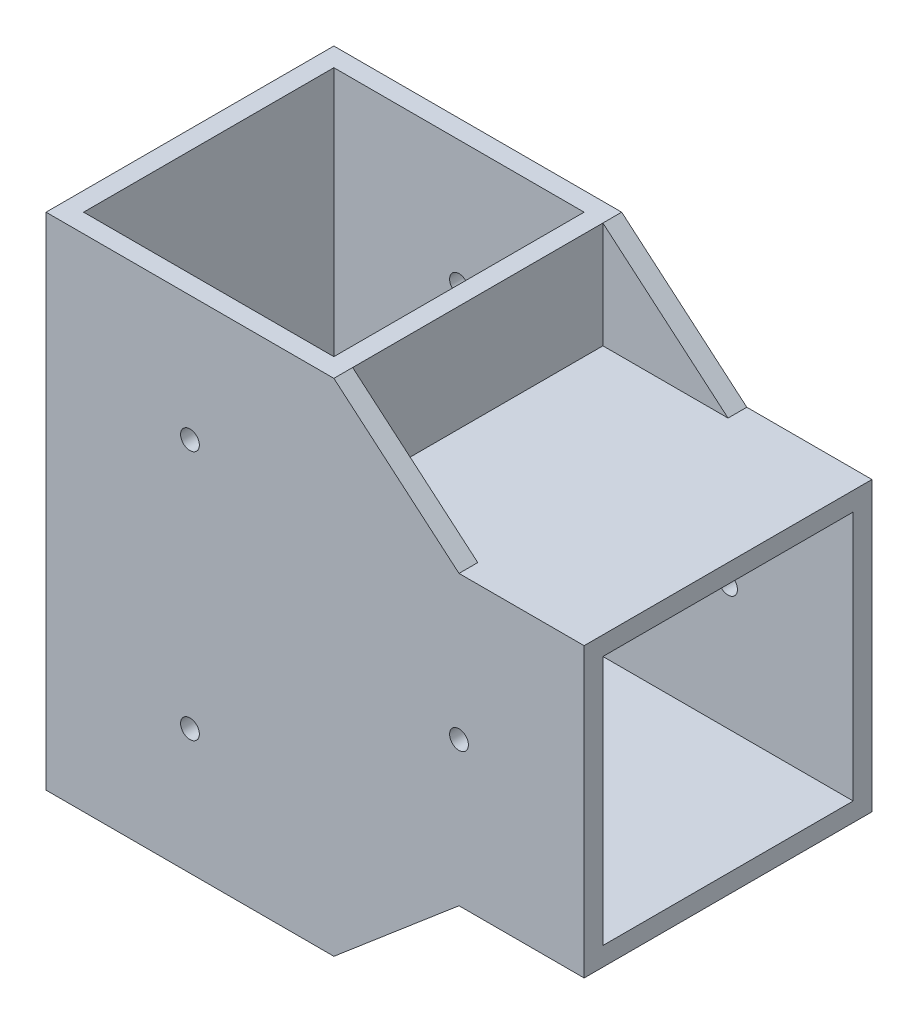
SolidWorks part; units mm, degrees
material "Nylon 6/10"
ref_plane "Front Plane" through (0, 0, 0) normal (0, 0, 1) x (1, 0, 0)
ref_plane "Top Plane" through (0, 0, 0) normal (0, 1, 0) x (1, 0, 0)
ref_plane "Right Plane" through (0, 0, 0) normal (1, 0, 0) x (0, 0, -1)
sketch "Esquisse1" plane through (0, 0, 0) normal (0, 0, 1) x (1, 0, 0)
  line L0 (-66, 40) -> (-20, 40)
  line L1 (-20, 40) -> (0, 23)
  line L2 (0, 23) -> (20, 23)
  line L3 (20, 23) -> (20, 0)
  line L4 (20, 0) -> (0, 0)
  line L5 (0, 0) -> (-66, 0)
  line L6 (-66, 0) -> (-66, 40)
  dimension "D1" = 23
  dimension "D2" = 40
  dimension "D3" = 20
  dimension "D4" = 40
  dimension "D5" = 46
  dimension "D6" = 20
extrude "Boss.-Extru.1" add sketch "Esquisse1" along normal blind 3
sketch "Esquisse2" plane through (0, 0, 3) normal (0, 0, 1) x (1, 0, 0)
  line L0 (20, 23) -> (-20, 23)
  line L1 (-20, 23) -> (-20, 40)
  line L2 (-20, 40) -> (-23, 40)
  line L3 (-20, 40) -> (-66, 40) construction
  line L4 (-23, 40) -> (-23, 0)
  line L5 (-66, 0) -> (20, 0) construction
  line L6 (-23, 0) -> (-20, 0)
  line L7 (-20, 0) -> (-20, 20)
  line L8 (-20, 20) -> (20, 20)
  line L9 (20, 20) -> (20, 23)
  line L11 (-66, 40) -> (-63, 40)
  line L12 (-66, 40) -> (-66, 0)
  line L13 (-66, 0) -> (-63, 0)
  line L14 (-63, 40) -> (-63, 0)
  dimension "D1" = 3
  dimension "D2" = 3
  dimension "D3" = 3
extrude "Boss.-Extru.2" add sketch "Esquisse2" along normal blind 20
mirror "Symétrie1" about plane through (20, 0, 3) normal (0, 1, 0) of bodies 102
mirror "Symétrie2" about plane through (0, 0, 23) normal (0, 0, 1) of bodies 103
sketch "Esquisse3" plane through (0, 0, 46) normal (0, 0, 1) x (1, 0, 0)
  line L0 (-43, 20) -> (-43, -20) construction
  circle A0 centre (-43, 20) radius 1.5
  circle A1 centre (-43, -20) radius 1.5
  circle A2 centre (0, 0) radius 1.5
  dimension "D1" = 3
  dimension "D5" = 3
  dimension "D2" = 40
  dimension "D3" = 20
  dimension "D4" = 20
extrude "Enlèv. mat.-Extru.1" cut sketch "Esquisse3" against normal through all both and the other way through all
